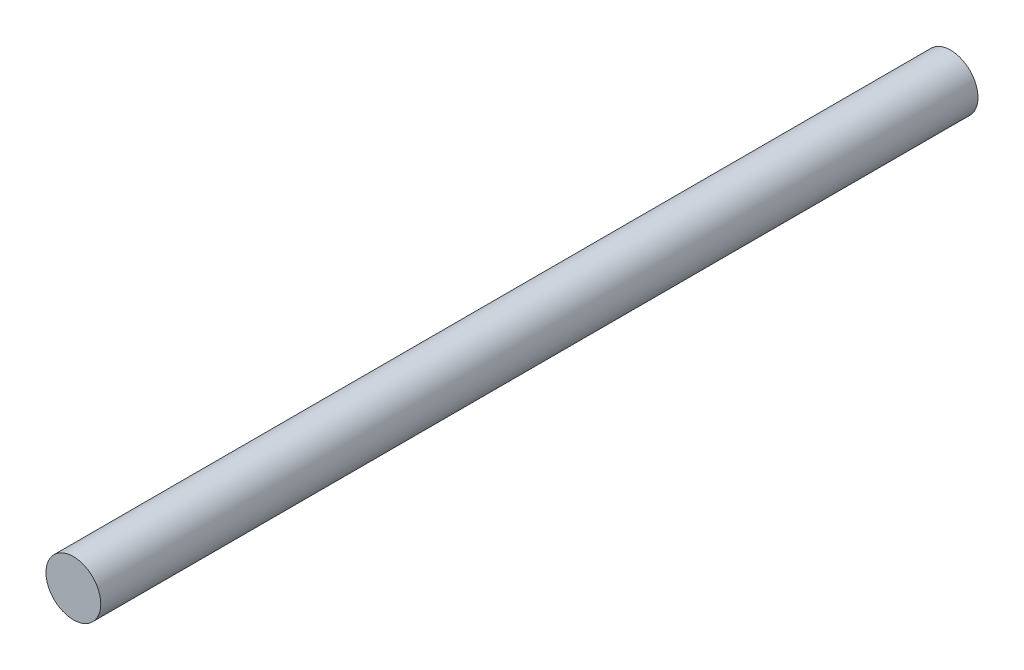
SolidWorks part; units mm, degrees
ref_plane "Front Plane" through (0, 0, 0) normal (0, 0, 1) x (1, 0, 0)
ref_plane "Top Plane" through (0, 0, 0) normal (0, 1, 0) x (1, 0, 0)
ref_plane "Right Plane" through (0, 0, 0) normal (1, 0, 0) x (0, 0, -1)
sketch "Sketch2" plane through (0, 0, 0) normal (0, 0, 1) x (1, 0, 0)
  circle A0 centre (-21.5564, 3.4901) radius 1
extrude "Boss-Extrude1" add sketch "Sketch2" along normal blind 32
